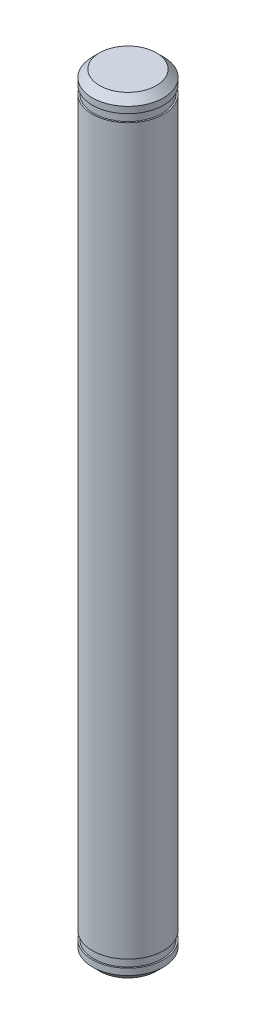
SolidWorks part; units mm, degrees
ref_plane "前视基准面" through (0, 0, 0) normal (0, 0, 1) x (1, 0, 0)
ref_plane "上视基准面" through (0, 0, 0) normal (0, 1, 0) x (1, 0, 0)
ref_plane "右视基准面" through (0, 0, 0) normal (1, 0, 0) x (0, 0, -1)
other "Configuration Table"
sketch "草图1" plane through (0, 0, 0) normal (0, 0, 1) x (1, 0, 0)
  line L0 (0, 17.9143) -> (0, -10.0949) construction
  line L1 (0, 54) -> (5, 54)
  line L2 (5, 54) -> (5, 15)
  line L4 (5, 15) -> (5, -15)
  line L6 (5, -15) -> (5, -54)
  line L7 (5, -54) -> (0, -54)
  line L8 (0, 0) -> (25.4592, 0) construction
  line L9 (0, 54) -> (0, -54)
  dimension "D1" = 5
  dimension "D3" = 30
  dimension "D4" = 39
  dimension "D5" = 39
revolve "旋转1" add sketch "草图1" angle 360 about L9
chamfer "倒角1" distance 1 angle 45 2 edges at (-5, -54, 0) (-5, 54, 0)
ref_plane "基准面1" through (0, 0, 0) normal (0, 1, 0) x (1, 0, 0)
sketch "草图2" plane through (0, 54, 0) normal (0, 1, 0) x (1, 0, 0)
  circle A0 centre (0, 0) radius 5 construction
  circle A1 centre (0, 0) radius 5
  circle A2 centre (0, 0) radius 4.8
  dimension "D1" = 9.6
extrude "切除-拉伸1" cut sketch "草图2" along normal blind 1.1 from offset 3 offset against normal yes
mirror "镜向1" about plane through (0, 0, 0) normal (0, 1, 0) of "切除-拉伸1"
